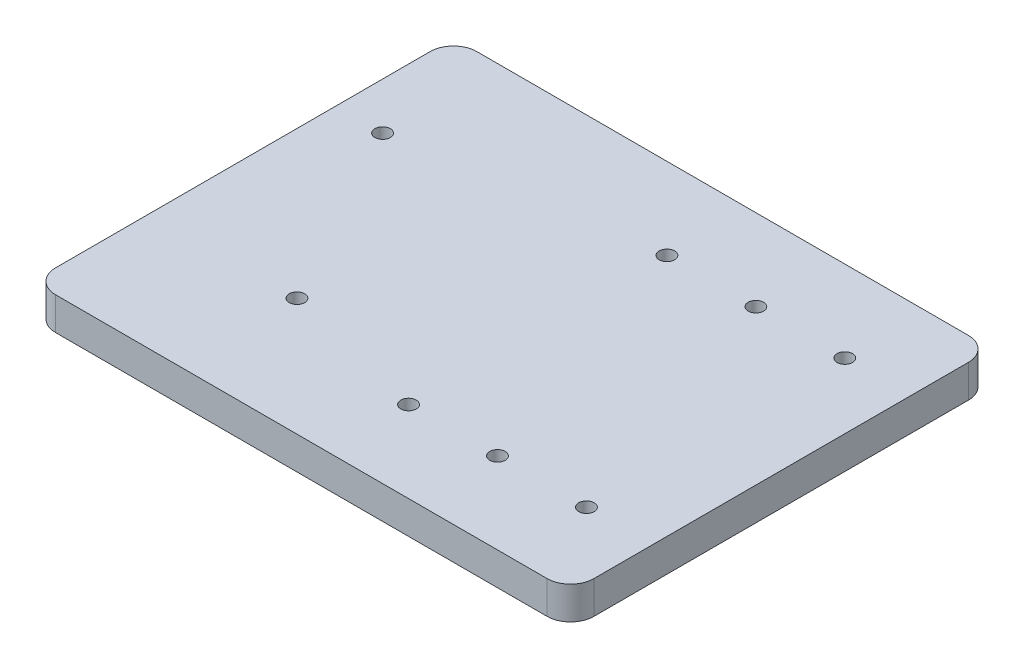
SolidWorks part; units mm, degrees
ref_plane "Front Plane" through (0, 0, 0) normal (0, 0, 1) x (1, 0, 0)
ref_plane "Top Plane" through (0, 0, 0) normal (0, 1, 0) x (1, 0, 0)
ref_plane "Right Plane" through (0, 0, 0) normal (1, 0, 0) x (0, 0, -1)
sketch "Sketch1" plane through (0, 0, 0) normal (0, 1, 0) x (1, 0, 0)
  line L1 (0, 0) -> (115, 0)
  line L2 (0, 0) -> (0, 90)
  line L3 (0, 90) -> (115, 90)
  line L4 (115, 0) -> (115, 90)
  circle A0 centre (10, 64.85) radius 1.65
  circle A1 centre (31.4, 25.15) radius 1.65
  dimension "D3" = 3.3
  dimension "D4" = 3.3
  dimension "D1" = 115
  dimension "D2" = 90
  dimension "D5" = 39.7
  dimension "D6" = 21.4
  dimension "D7" = 25.15
  dimension "D8" = 10
extrude "Boss-Extrude2" add sketch "Sketch1" along normal blind 7
sketch "Sketch5" plane through (0, 0, 0) normal (0, -1, 0) x (-1, 0, 0)
  line L0 (-115, 0) -> (-115, 90) construction
  line L1 (0, 90) -> (0, 0) construction
  line L2 (-115, 90) -> (0, 90) construction
  circle A0 centre (-101, 17.4) radius 1.65
  circle A1 centre (-101, 72.6) radius 1.65
  circle A4 centre (-82, 17.4) radius 1.65
  circle A5 centre (-82, 72.6) radius 1.65
  circle A6 centre (-63, 17.4) radius 1.65
  circle A7 centre (-63, 72.6) radius 1.65
  dimension "D1" = 3.3
  dimension "D2" = 3.3
  dimension "D7" = 3.3
  dimension "D8" = 3.3
  dimension "D9" = 19
  dimension "D10" = 3.3
  dimension "D11" = 3.3
  dimension "D3" = 55.2
  dimension "D4" = 14
  dimension "D5" = 17.4
  dimension "D6" = 19
extrude "Cut-Extrude4" cut sketch "Sketch5" against normal through all both and the other way through all
fillet "Fillet1" radius 5 4 edges at (115, 3.5, 0) (115, 3.5, -90) (0, 3.5, -90) (0, 3.5, 0)
sketch "Sketch8" plane through (0, 0, 0) normal (0, -1, 0) x (1, 0, 0)
  circle A0 centre (31.4, -25.15) radius 3.5
  circle A1 centre (10, -64.85) radius 3.5
  circle A2 centre (63, -72.6) radius 3.5
  circle A3 centre (82, -72.6) radius 3.5
  circle A4 centre (101, -72.6) radius 3.5
  circle A5 centre (63, -17.4) radius 3.5
  circle A6 centre (82, -17.4) radius 3.5
  circle A7 centre (101, -17.4) radius 3.5
  dimension "D1" = 7
  dimension "D2" = 7
  dimension "D3" = 7
  dimension "D4" = 7
  dimension "D5" = 7
  dimension "D6" = 7
  dimension "D7" = 7
  dimension "D8" = 7
extrude "Cut-Extrude6" cut sketch "Sketch8" against normal blind 4
